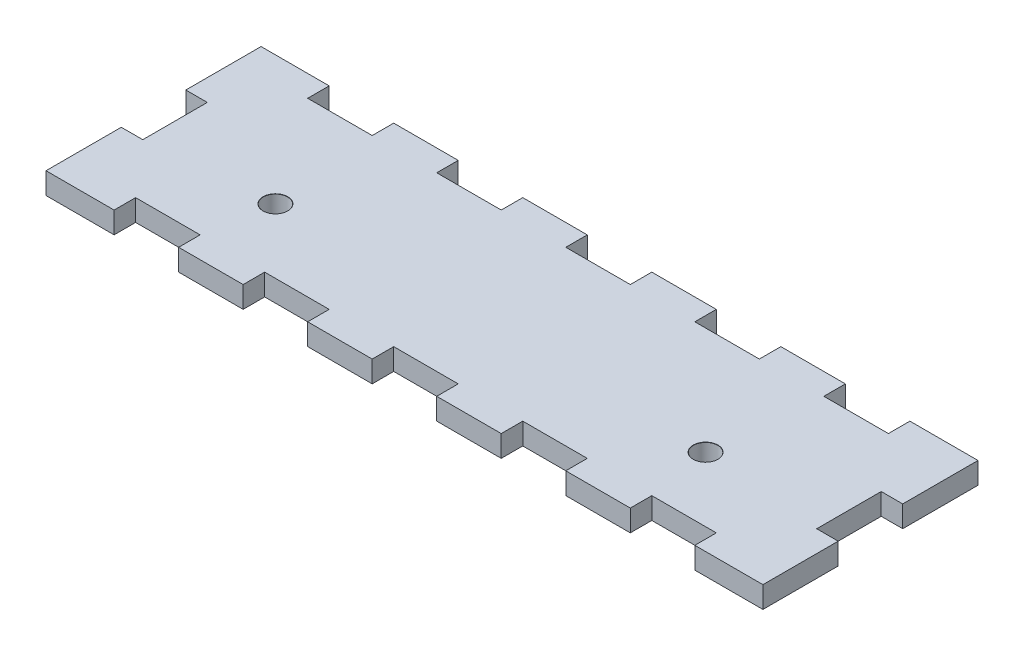
SolidWorks part; units mm, degrees
ref_plane "Front Plane" through (0, 0, 0) normal (0, 0, 1) x (1, 0, 0)
ref_plane "Top Plane" through (0, 0, 0) normal (0, 1, 0) x (1, 0, 0)
ref_plane "Right Plane" through (0, 0, 0) normal (1, 0, 0) x (0, 0, -1)
sketch "Sketch1" plane through (0, 0, 0) normal (0, 1, 0) x (1, 0, 0)
  line L0 (50, 15) -> (47, 15)
  line L1 (47, 15) -> (40.5, 15)
  line L2 (40.5, 15) -> (40.5, 12)
  line L3 (40.5, 12) -> (31.5, 12)
  line L4 (31.5, 12) -> (31.5, 15)
  line L5 (31.5, 15) -> (22.5, 15)
  line L6 (22.5, 15) -> (22.5, 12)
  line L7 (22.5, 12) -> (13.5, 12)
  line L8 (13.5, 12) -> (13.5, 15)
  line L9 (13.5, 15) -> (4.5, 15)
  line L10 (4.5, 15) -> (4.5, 12)
  line L11 (4.5, 12) -> (-4.5, 12)
  line L12 (-4.5, 12) -> (-4.5, 15)
  line L13 (-4.5, 15) -> (-13.5, 15)
  line L14 (-13.5, 15) -> (-13.5, 12)
  line L15 (-13.5, 12) -> (-22.5, 12)
  line L16 (-22.5, 12) -> (-22.5, 15)
  line L17 (-22.5, 15) -> (-31.5, 15)
  line L18 (-31.5, 15) -> (-31.5, 12)
  line L19 (-31.5, 12) -> (-40.5, 12)
  line L20 (-40.5, 12) -> (-40.5, 15)
  line L21 (-40.5, 15) -> (-47, 15)
  line L22 (-47, 15) -> (-50, 15)
  line L23 (-50, 15) -> (-50, 12)
  line L24 (-50, 12) -> (-50, 4.5)
  line L25 (-50, 4.5) -> (-47, 4.5)
  line L26 (-47, 4.5) -> (-47, -4.5)
  line L27 (-47, -4.5) -> (-50, -4.5)
  line L28 (-50, -4.5) -> (-50, -12)
  line L29 (-50, -12) -> (-50, -15)
  line L30 (-50, -15) -> (-47, -15)
  line L31 (-47, -15) -> (-40.5, -15)
  line L32 (-40.5, -15) -> (-40.5, -12)
  line L33 (-40.5, -12) -> (-31.5, -12)
  line L34 (-31.5, -12) -> (-31.5, -15)
  line L35 (-31.5, -15) -> (-22.5, -15)
  line L36 (-22.5, -15) -> (-22.5, -12)
  line L37 (-22.5, -12) -> (-13.5, -12)
  line L38 (-13.5, -12) -> (-13.5, -15)
  line L39 (-13.5, -15) -> (-4.5, -15)
  line L40 (-4.5, -15) -> (-4.5, -12)
  line L41 (-4.5, -12) -> (4.5, -12)
  line L42 (4.5, -12) -> (4.5, -15)
  line L43 (4.5, -15) -> (13.5, -15)
  line L44 (13.5, -15) -> (13.5, -12)
  line L45 (13.5, -12) -> (22.5, -12)
  line L46 (22.5, -12) -> (22.5, -15)
  line L47 (22.5, -15) -> (31.5, -15)
  line L48 (31.5, -15) -> (31.5, -12)
  line L49 (31.5, -12) -> (40.5, -12)
  line L50 (40.5, -12) -> (40.5, -15)
  line L51 (40.5, -15) -> (47, -15)
  line L52 (47, -15) -> (50, -15)
  line L53 (50, -15) -> (50, -12)
  line L54 (50, -12) -> (50, -4.5)
  line L55 (50, -4.5) -> (47, -4.5)
  line L56 (47, -4.5) -> (47, 4.5)
  line L57 (47, 4.5) -> (50, 4.5)
  line L58 (50, 4.5) -> (50, 12)
  line L59 (50, 12) -> (50, 15)
  line L60 (-50, 15) -> (50, -15) construction
  point P60 (0, 0)
extrude "Boss-Extrude1" add sketch "Sketch1" along normal mid plane 3
sketch "Sketch2" plane through (0, 1.5, 0) normal (0, 1, 0) x (1, 0, 0)
  text T0 "Left/Right\r\n"
extrude "Cut-Extrude1" [suppressed] cut sketch "Sketch2" against normal blind 1
sketch "Sketch3" plane through (0, 1.5, 0) normal (0, 1, 0) x (1, 0, 0)
  line L0 (-30, -3) -> (30, -3) construction
  line L1 (-50, 15) -> (-50, 4.5) construction
  line L3 (4.5, -15) -> (13.5, -15) construction
  point P0 (-30, -3)
  point P1 (30, -3)
  point P2 (0, -3)
  point P8 (9, -15)
  dimension "D1" = 20
  dimension "D2" = 12
hole_wizard "M3 Clearance Hole1" positions "Sketch3" profile "Sketch4" hole size "M3" standard "ISO" end condition through all
sketch "Sketch4" plane through (-30, 1.5, 3) normal (1, 0, 0) x (0, 0, 1)
  line L0 (0, 0) -> (0, 3)
  line L1 (0, 3) -> (1.7, 3)
  line L2 (1.7, 3) -> (1.7, 0.025)
  line L3 (1.7, 0.025) -> (1.725, 0)
  line L5 (1.725, 0) -> (0, 0)
  line L6 (-1.7, 0.025) -> (-1.725, 0) construction
  line L11 (0, -6.35) -> (0, 107.95) construction
  dimension "Thru Hole Dia." = 3.4
  dimension "Thru Hole Depth" = 3
  dimension "Near C'Sink Dia." = 3.45
  dimension "Near C'Sink Angle" = 90
